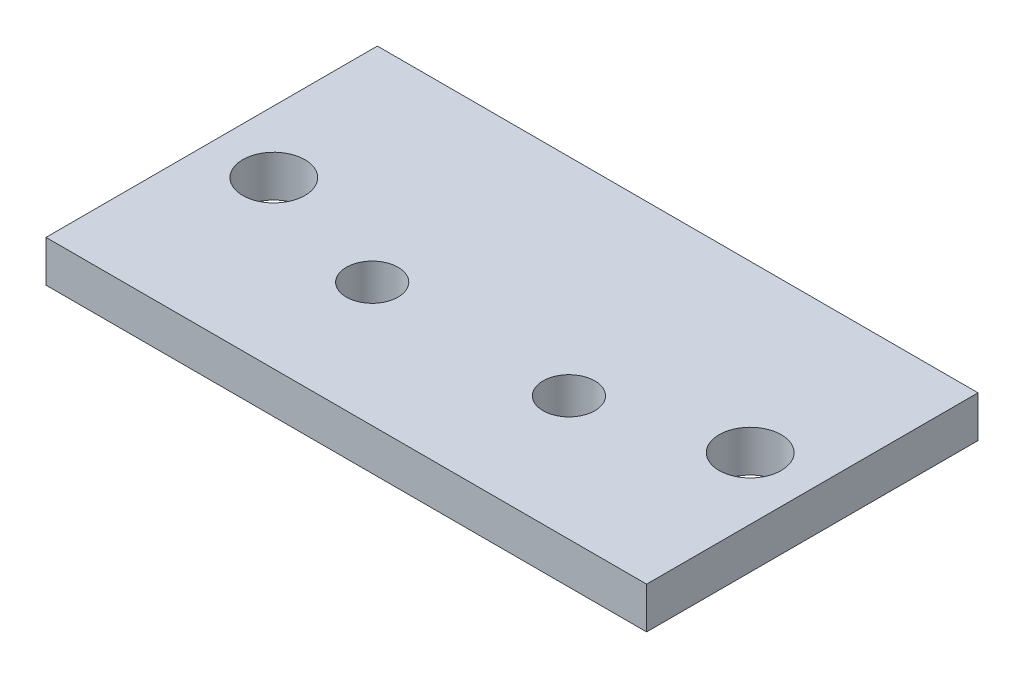
SolidWorks part; units mm, degrees
ref_plane "Alzado" through (0, 0, 0) normal (0, 0, 1) x (1, 0, 0)
ref_plane "Planta" through (0, 0, 0) normal (0, 1, 0) x (1, 0, 0)
ref_plane "Vista lateral" through (0, 0, 0) normal (1, 0, 0) x (0, 0, -1)
sketch "Croquis1" plane through (0, 0, 0) normal (0, 1, 0) x (1, 0, 0)
  line L0 (14.5, 8) -> (14.5, 0) construction
  line L2 (14.5, -8) -> (14.5, 8)
  line L3 (14.5, 8) -> (-14.5, 8)
  line L4 (-14.5, -8) -> (-14.5, 8)
  line L5 (14.5, -8) -> (-14.5, 8) construction
  line L6 (14.5, 8) -> (-14.5, -8) construction
  line L7 (14.5, 0) -> (11.5, 0) construction
  line L8 (0, 8) -> (0, -8) construction
  line L9 (-14.5, -8) -> (14.5, -8)
  line L10 (0, -8) -> (10, -8) construction
  line L11 (-10, -8) -> (-10, 2) construction
  line L12 (-10, 2) -> (10, 2) construction
  line L13 (10, 2) -> (10, -8) construction
  line L14 (-10, -8) -> (-4.75, -8) construction
  line L15 (-4.75, -8) -> (-4.75, -2) construction
  circle A0 centre (11.5, 0) radius 1.5
  circle A1 centre (-11.5, 0) radius 1.5
  circle A2 centre (-4.75, -2) radius 1.25
  circle A3 centre (4.75, -2) radius 1.25
  point P0 (0, 0)
  dimension "D3" = 3
  dimension "D4" = 2.5
  dimension "D1" = 29
  dimension "D2" = 16
extrude "Saliente-Extruir1" add sketch "Croquis1" along normal blind 2
